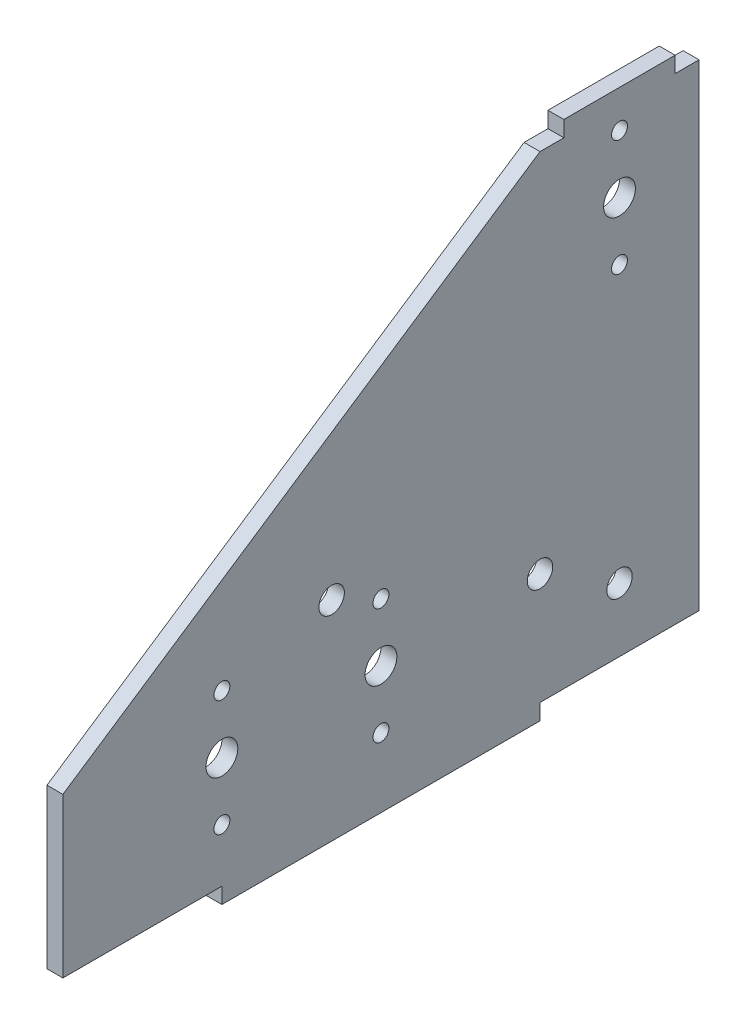
SolidWorks part; units mm, degrees
ref_plane "Alzado" through (0, 0, 0) normal (0, 0, 1) x (1, 0, 0)
ref_plane "Planta" through (0, 0, 0) normal (0, 1, 0) x (1, 0, 0)
ref_plane "Vista lateral" through (0, 0, 0) normal (1, 0, 0) x (0, 0, -1)
sketch "Croquis1" plane through (0, 0, 0) normal (1, 0, 0) x (0, 0, -1)
  line L0 (150, 150) -> (0, 50)
  line L1 (0, 0) -> (50, 0)
  line L2 (0, 0) -> (0, 50)
  line L3 (150, 150) -> (157.5, 150)
  line L4 (200, 0) -> (200, 150)
  line L5 (200, 75) -> (37.5, 75) construction
  line L6 (175, 155) -> (175, 0) construction
  line L7 (100, 116.6667) -> (100, -5) construction
  line L8 (84.5, 106.3333) -> (84.5, -5) construction
  line L9 (50, 0) -> (50, -5)
  line L10 (50, -5) -> (150, -5)
  line L11 (150, 0) -> (150, -5)
  line L12 (154, 35) -> (0, 35) construction
  line L13 (192.5, 150) -> (200, 150)
  line L14 (150, 0) -> (200, 0)
  line L16 (157.5, 150) -> (157.5, 155)
  line L17 (157.5, 155) -> (192.5, 155)
  line L18 (192.5, 150) -> (192.5, 155)
  circle A0 centre (175, 125) radius 5
  circle A1 centre (175, 20) radius 4
  circle A2 centre (150, 35) radius 4
  circle A3 centre (175, 143.25) radius 2.5
  circle A4 centre (175, 106.75) radius 2.5
  circle A5 centre (100, 35) radius 5
  circle A6 centre (84.5, 60.6856) radius 4
  circle A7 centre (100, 53.25) radius 2.5
  circle A8 centre (100, 16.75) radius 2.5
  circle A13 centre (50, 35) radius 5
  circle A14 centre (50, 53.25) radius 2.5
  circle A15 centre (50, 16.75) radius 2.5
  dimension "D6" = 10
  dimension "D10" = 8
  dimension "D12" = 8
  dimension "D15" = 5
  dimension "D16" = 5
  dimension "D20" = 40
  dimension "D22" = 2
  dimension "D23" = 10
  dimension "D24" = 5
  dimension "D21" = 8
  dimension "D1" = 150
  dimension "D2" = 200
  dimension "D3" = 50
  dimension "D4" = 50
  dimension "D5" = 50
  dimension "D7" = 100
  dimension "D8" = 50
  dimension "D9" = 5
  dimension "D11" = 20
  dimension "D13" = 25
  dimension "D14" = 15
  dimension "D17" = 18.25
  dimension "D18" = 18.25
  dimension "D19" = 30
  dimension "D25" = 2
  dimension "D26" = 15.5
  dimension "D31" = 35
  dimension "D32" = 5
  dimension "D38" = 7.5
extrude "Saliente-Extruir1" add sketch "Croquis1" along normal blind 5
